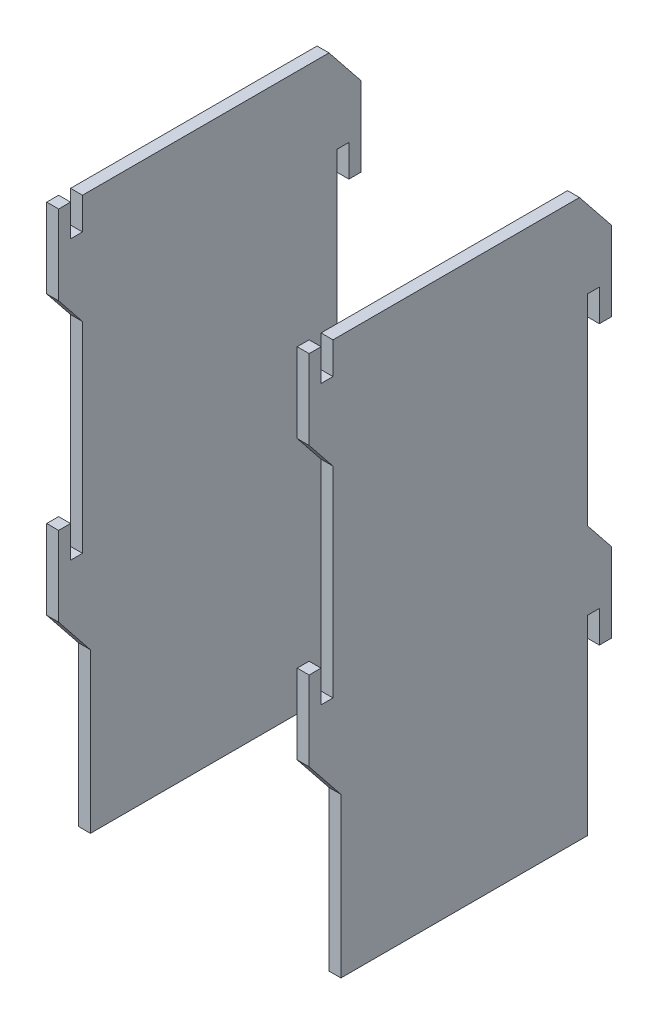
SolidWorks part; units mm, degrees
ref_plane "前视基准面" through (0, 0, 0) normal (0, 0, 1) x (1, 0, 0)
ref_plane "上视基准面" through (0, 0, 0) normal (0, 1, 0) x (1, 0, 0)
ref_plane "右视基准面" through (0, 0, 0) normal (1, 0, 0) x (0, 0, -1)
sketch "草图2" plane through (0, 0, 0) normal (1, 0, 0) x (0, 0, -1)
  line L0 (0, 140) -> (-2, 140)
  line L1 (0, 0) -> (60, 0)
  line L2 (0, 0) -> (0, 40)
  line L3 (0, 140) -> (60, 140)
  line L5 (-8, 140) -> (-8, 120)
  line L6 (-8, 120) -> (-2, 112.5)
  line L7 (-5, 140) -> (-8, 140)
  line L9 (-5, 140) -> (-5, 132)
  line L10 (-5, 132) -> (-2, 132)
  line L11 (-2, 140) -> (-2, 132)
  line L13 (-8, 70) -> (-8, 50)
  line L14 (-8, 50) -> (0, 40)
  line L15 (-5, 70) -> (-8, 70)
  line L16 (-5, 70) -> (-5, 62)
  line L17 (-5, 62) -> (-2, 62)
  line L18 (-2, 70) -> (-2, 62)
  line L20 (60, 140) -> (68, 130)
  line L21 (68, 130) -> (68, 110)
  line L22 (68, 110) -> (65, 110)
  line L25 (62, 110) -> (62, 118)
  line L26 (62, 118) -> (65, 118)
  line L27 (65, 110) -> (65, 118)
  line L28 (62, 67.5) -> (68, 60)
  line L29 (68, 60) -> (68, 40)
  line L30 (68, 40) -> (65, 40)
  line L32 (62, 40) -> (62, 48)
  line L33 (62, 48) -> (65, 48)
  line L34 (65, 40) -> (65, 48)
  line L36 (62, 110) -> (62, 67.5)
  line L37 (-2, 70) -> (-2, 112.5)
  line L38 (62, 40) -> (62, 0)
  line L39 (62, 0) -> (60, 0)
  dimension "D1" = 140
  dimension "D2" = 60
  dimension "D3" = 8
  dimension "D4" = 20
  dimension "D5" = 7.5
  dimension "D6" = 8
  dimension "D7" = 3
  dimension "D8" = 2
  dimension "D9" = 7.5
  dimension "D10" = 20
  dimension "D11" = 10
  dimension "D12" = 8
  dimension "D13" = 3
  dimension "D15" = 40
  dimension "D16" = 8
  dimension "D17" = 10
  dimension "D18" = 20
  dimension "D19" = 3
  dimension "D21" = 8
  dimension "D23" = 20
  dimension "D26" = 3
  dimension "D27" = 8
  dimension "D28" = 40
extrude "凸台-拉伸1" add sketch "草图2" along normal blind 66
sketch "草图3" plane through (0, 0, -62) normal (0, 0, -1) x (-1, 0, 0)
  line L0 (-66, 140) -> (0, 140) construction
  line L1 (-63, 140) -> (-3, 140)
  line L2 (-63, 140) -> (-63, 0)
  line L3 (-63, 0) -> (-3, 0)
  line L4 (-3, 140) -> (-3, 0)
  line L5 (-66, 0) -> (0, 0) construction
  line L6 (0, 130) -> (0, 140) construction
  dimension "D1" = 3
  dimension "D2" = 3
extrude "切除-拉伸1" cut sketch "草图3" against normal through all both and the other way through all
sketch "草图4" plane through (0, 0, -62) normal (0, 0, -1) x (-1, 0, 0)
  line L0 (-63, 118) -> (-66, 118)
  line L2 (-63, 128) -> (-63, 118)
  line L3 (-63, 0) -> (-3, 0)
  line L5 (-66, 118) -> (-66, 128)
  line L6 (-66, 128) -> (-69, 128)
  line L7 (-69, 128) -> (-69, 113)
  line L8 (-63, 107) -> (-63, 48)
  line L9 (-69, 113) -> (-63, 107)
  line L11 (-63, 128) -> (-60, 128)
  line L12 (-60, 128) -> (-60, 113)
  line L13 (-60, 113) -> (-60, 98)
  line L14 (-60, 98) -> (-6, 98)
  line L15 (-63, 48) -> (-66, 48)
  line L16 (-66, 48) -> (-66, 58)
  line L17 (-66, 58) -> (-69, 58)
  line L18 (-69, 58) -> (-69, 43)
  line L19 (-69, 43) -> (-63, 37)
  line L20 (-66, 48) -> (-63, 48) construction
  line L21 (3, 43) -> (-3, 37)
  line L22 (3, 58) -> (3, 43)
  line L23 (0, 58) -> (3, 58)
  line L24 (0, 48) -> (0, 58)
  line L25 (-3, 48) -> (0, 48)
  line L26 (-6, 113) -> (-6, 98)
  line L27 (-6, 128) -> (-6, 113)
  line L28 (-3, 128) -> (-6, 128)
  line L29 (3, 113) -> (-3, 107)
  line L30 (-3, 107) -> (-3, 48)
  line L31 (3, 128) -> (3, 113)
  line L32 (0, 128) -> (3, 128)
  line L33 (0, 118) -> (0, 128)
  line L34 (-3, 128) -> (-3, 118)
  line L35 (-3, 118) -> (0, 118)
  line L36 (-63, 37) -> (-63, 0)
  line L37 (-3, 37) -> (-3, 0)
  dimension "D1" = 10
  dimension "D2" = 3
  dimension "D3" = 6
  dimension "D4" = 15
  dimension "D5" = 3
  dimension "D6" = 30
  dimension "D7" = 10
  dimension "D8" = 3
  dimension "D9" = 6
  dimension "D10" = 15
